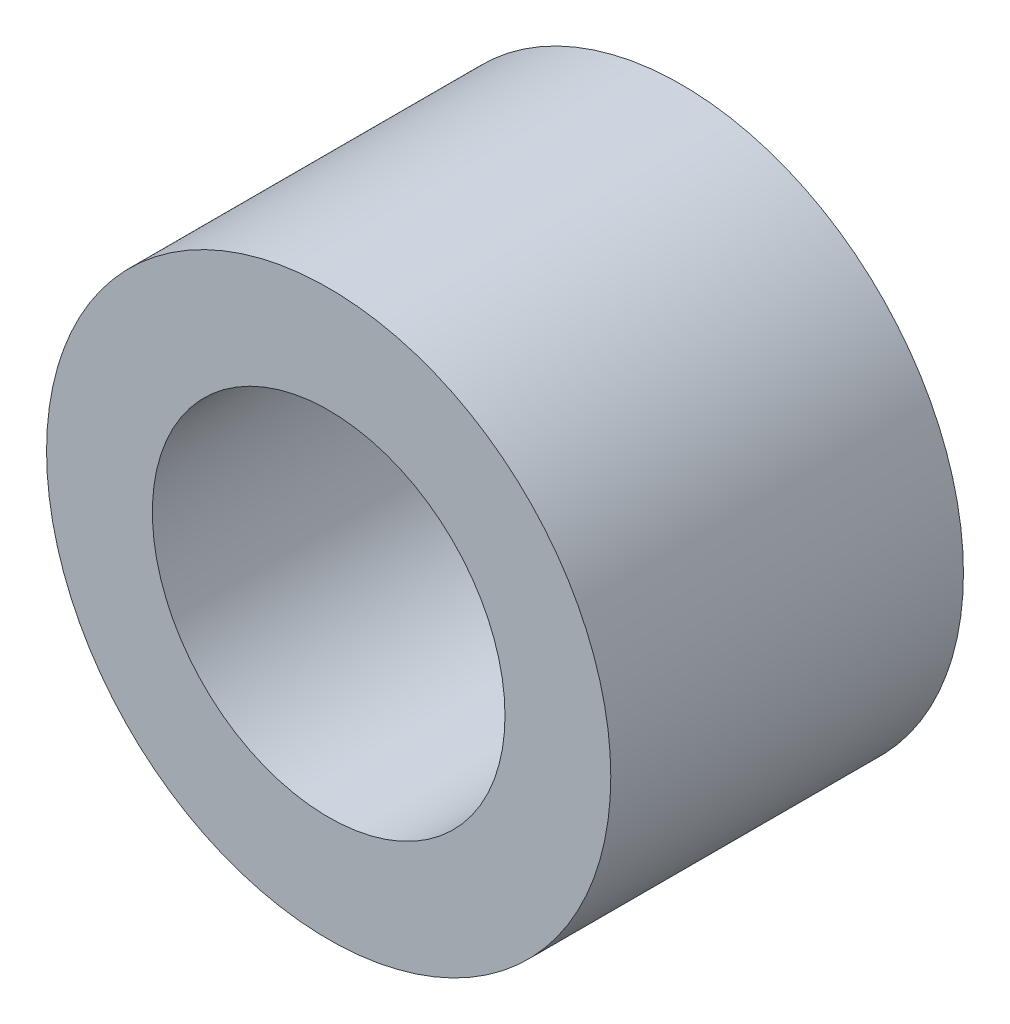
SolidWorks part; units mm, degrees
ref_plane "Plan de face" through (0, 0, 0) normal (0, 0, 1) x (1, 0, 0)
ref_plane "Plan de dessus" through (0, 0, 0) normal (0, 1, 0) x (1, 0, 0)
ref_plane "Plan de droite" through (0, 0, 0) normal (1, 0, 0) x (0, 0, -1)
sketch "Esquisse1" plane through (0, 0, 0) normal (0, 0, 1) x (1, 0, 0)
  circle A0 centre (0, 0) radius 4
  dimension "D1" = 8
extrude "Boss.-Extru.1" add sketch "Esquisse1" along normal blind 5
sketch "Esquisse2" plane through (0, 0, 5) normal (0, 0, 1) x (1, 0, 0)
  circle A0 centre (0, 0) radius 2.5
  dimension "D1" = 5
extrude "Enlèv. mat.-Extru.1" cut sketch "Esquisse2" against normal through all
